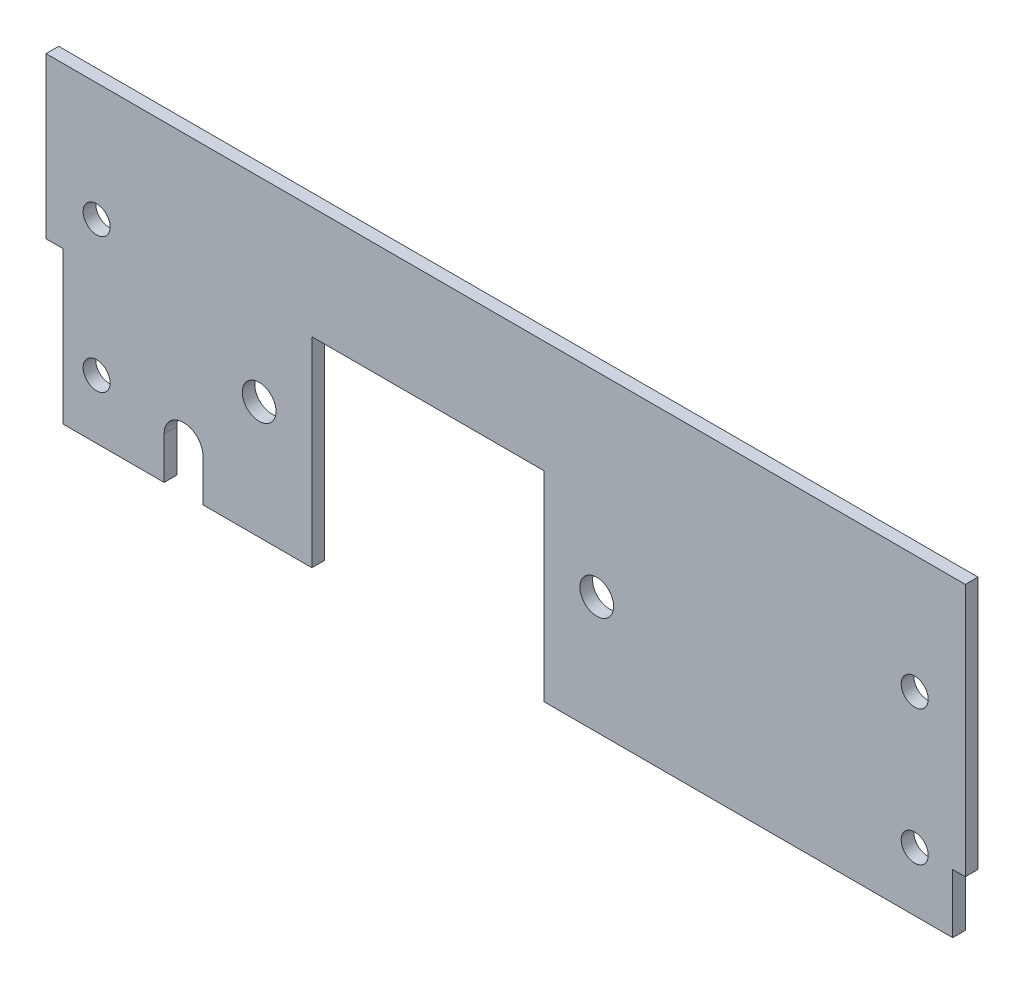
SolidWorks part; units mm, degrees
ref_plane "Front Plane" through (0, 0, 0) normal (0, 0, 1) x (1, 0, 0)
ref_plane "Top Plane" through (0, 0, 0) normal (0, 1, 0) x (1, 0, 0)
ref_plane "Right Plane" through (0, 0, 0) normal (1, 0, 0) x (0, 0, -1)
sketch "Sketch1" plane through (0, 0, 0) normal (0, 0, 1) x (1, 0, 0)
  line L0 (110.9147, 563.0809) -> (110.9147, 588.0809) construction
  line L1 (110.9147, 561.0809) -> (0, 561.0809)
  line L2 (110.9147, 561.0809) -> (110.9147, 598.0809)
  line L3 (110.9147, 598.0809) -> (0, 598.0809)
  line L4 (0, 561.0809) -> (0, 598.0809)
  circle A0 centre (103.9147, 584.0809) radius 1.6 construction
  circle A1 centre (103.9147, 568.0809) radius 1.6 construction
  circle A2 centre (7, 584.0809) radius 1.6 construction
  circle A3 centre (7, 568.0809) radius 1.6 construction
  circle A4 centre (103.9147, 584.0809) radius 1.6
  circle A5 centre (103.9147, 568.0809) radius 1.6
  circle A6 centre (7, 584.0809) radius 1.6
  circle A7 centre (7, 568.0809) radius 1.6
  dimension "D1" = 37
extrude "Boss-Extrude1" add sketch "Sketch1" along normal blind 1.5
sketch "Sketch2" plane through (0, 0, 1.5) normal (0, 0, 1) x (1, 0, 0)
  line L1 (0, 561.0809) -> (3, 561.0809)
  line L2 (0, 561.0809) -> (0, 579.0809)
  line L3 (0, 579.0809) -> (3, 579.0809)
  line L4 (3, 561.0809) -> (3, 579.0809)
  dimension "D1" = 3
  dimension "D2" = 18
extrude "Cut-Extrude1" cut sketch "Sketch2" against normal blind 1.5
sketch "Sketch3" plane through (0, 0, 1.5) normal (0, 0, 1) x (1, 0, 0)
  line L0 (3, 579.0809) -> (0, 579.0809) construction
  line L1 (0, 598.0809) -> (1, 598.0809)
  line L2 (0, 598.0809) -> (0, 579.0809)
  line L3 (0, 579.0809) -> (1, 579.0809)
  line L4 (1, 598.0809) -> (1, 579.0809)
  line L5 (3, 561.0809) -> (110.9147, 561.0809) construction
  line L6 (110.9147, 598.0809) -> (109.9147, 598.0809)
  line L7 (110.9147, 598.0809) -> (110.9147, 561.0809)
  line L8 (110.9147, 561.0809) -> (109.9147, 561.0809)
  line L9 (109.9147, 598.0809) -> (109.9147, 561.0809)
  line L12 (110.9147, 561.0809) -> (108.4147, 561.0809)
  line L13 (110.9147, 561.0809) -> (110.9147, 568.0809)
  line L14 (110.9147, 568.0809) -> (108.4147, 568.0809)
  line L15 (108.4147, 561.0809) -> (108.4147, 568.0809)
  line M5 (0, 579.0809) -> (3, 579.0809)
  line M7 (3, 561.0809) -> (110.9147, 561.0809)
  line M8 (110.9147, 561.0809) -> (110.9147, 598.0809)
  line M9 (110.9147, 598.0809) -> (0, 598.0809)
  line M10 (0, 598.0809) -> (0, 579.0809)
  dimension "D1" = 1
  dimension "D2" = 2.5
  dimension "D3" = 7
extrude "Cut-Extrude2" cut sketch "Sketch3" against normal blind 10 contours L15 L9 L14 M7 | L14 L9 M8 M7 | L14 L7 L9 M9 | L4 M9 M10 M5
sketch "Sketch4" plane through (0, 0, 1.5) normal (0, 0, 1) x (1, 0, 0)
  line L0 (3, 561.0809) -> (108.4147, 561.0809) construction
  line L1 (32.5, 584.7809) -> (60, 584.7809)
  line L2 (32.5, 584.7809) -> (32.5, 561.0809)
  line L3 (32.5, 561.0809) -> (60, 561.0809)
  line L4 (60, 584.7809) -> (60, 561.0809)
  line L5 (3, 561.0809) -> (3, 579.0809) construction
  line L6 (26.25, 574.9809) -> (66.25, 574.9809) construction
  line L7 (46.25, 584.7809) -> (46.25, 574.9809) construction
  line L8 (17.3, 561.0809) -> (17.3, 566.0809) construction
  line L9 (15, 561.0809) -> (15, 566.0809)
  line L10 (19.6, 561.0809) -> (19.6, 566.0809)
  circle A0 centre (66.25, 574.9809) radius 2
  circle A1 centre (26.25, 574.9809) radius 2
  arc A2 (15, 561.0809) -> (19.6, 561.0809) centre (17.3, 561.0809) ccw
  arc A3 (19.6, 566.0809) -> (15, 566.0809) centre (17.3, 566.0809) ccw
  point P16 (17.3, 563.5809)
  dimension "D5" = 4
  dimension "D7" = 2.3
  dimension "D1" = 27.5
  dimension "D2" = 23.7
  dimension "D3" = 29.5
  dimension "D4" = 40
  dimension "D6" = 9.8
  dimension "D8" = 12
  dimension "D9" = 5
extrude "Cut-Extrude3" cut sketch "Sketch4" against normal blind 10
